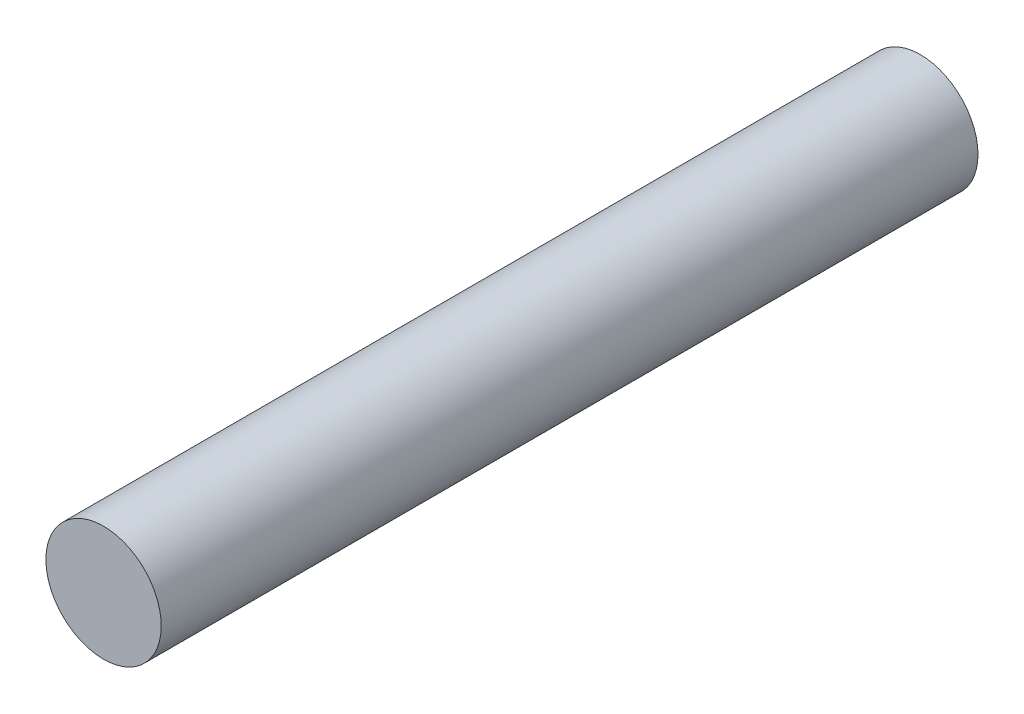
SolidWorks part; units mm, degrees
ref_plane "Alzado" through (0, 0, 0) normal (0, 0, 1) x (1, 0, 0)
ref_plane "Planta" through (0, 0, 0) normal (0, 1, 0) x (1, 0, 0)
ref_plane "Vista lateral" through (0, 0, 0) normal (1, 0, 0) x (0, 0, -1)
sketch "Croquis1" plane through (0, 0, 0) normal (0, 0, 1) x (1, 0, 0)
  circle A0 centre (0, 0) radius 6
  dimension "D1" = 12
extrude "Saliente-Extruir1" add sketch "Croquis1" along normal blind 85
